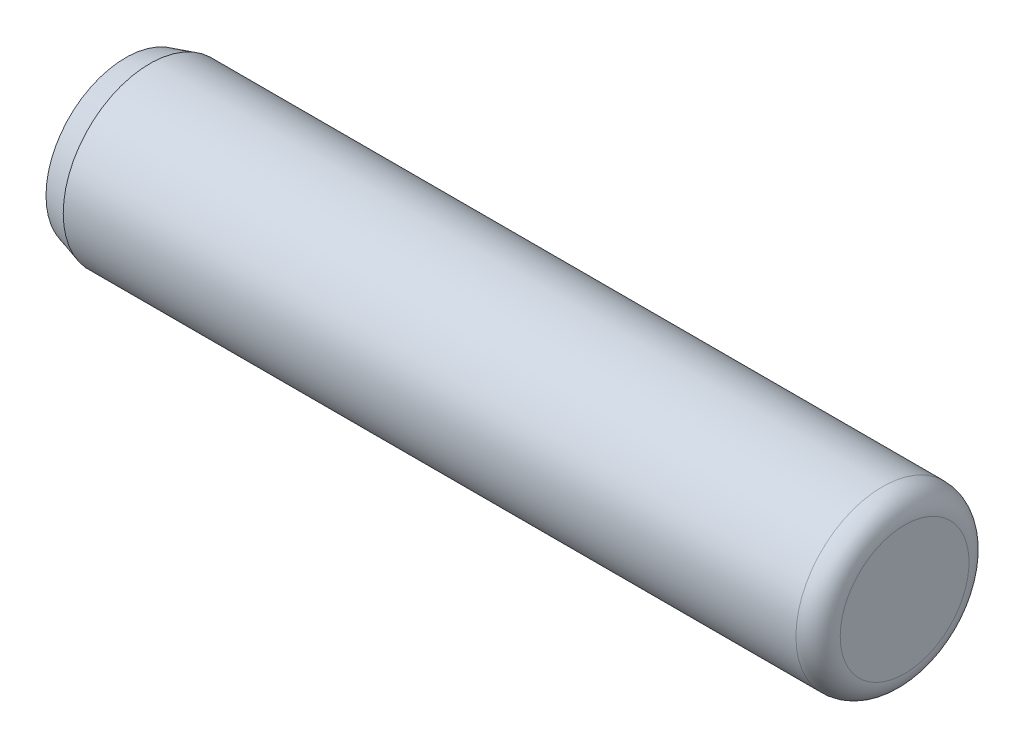
SolidWorks part; units mm, degrees
ref_plane "Front" through (0, 0, 0) normal (0, 0, 1) x (1, 0, 0)
ref_plane "Top" through (0, 0, 0) normal (0, 1, 0) x (1, 0, 0)
ref_plane "Right" through (0, 0, 0) normal (1, 0, 0) x (0, 0, -1)
sketch "Sketch1" plane through (0, 0, 0) normal (1, 0, 0) x (0, 0, -1)
  circle A0 centre (0, 0) radius 1.5875 construction
  point P3 (0, 1.5875)
  dimension "Diameter" = 3.175
sketch "Sketch2" plane through (0, 0, 0) normal (0, 0, 1) x (1, 0, 0)
  line L0 (-7.1438, 0) -> (7.1438, 0) construction
  line L1 (7.1438, 1.1811) -> (7.1438, -0.6481) construction
  line L2 (-7.1437, 1.4605) -> (-7.1437, -1.4605) construction
  line L3 (-7.1437, 1.4605) -> (-7.1437, 1.5875) construction
  line L4 (-7.1437, -1.4605) -> (-7.1437, -1.5875) construction
  line L5 (-7.1437, 1.4605) -> (-6.7008, 1.5875) construction
  line L6 (-6.7008, 1.5875) -> (6.7373, 1.5875) construction
  arc A0 (6.7373, 1.5875) -> (7.1438, 1.1811) centre (6.7373, 1.1811) cw construction
  point P6 (-3.9688, 0)
  point P8 (3.9688, 0)
  point P23 (6.1024, 1.5875)
  dimension "Crown Radius" = 0.4064
  dimension "Length" = 14.2875
  dimension "D1" = 3.175
  dimension "D2" = 3.175
  dimension "Point Diameter" = 2.921
  dimension "D3" = 16
  dimension "Crown Height" = 1.0414
sketch "Sketch3" plane through (0, 0, 0) normal (0, 0, 1) x (1, 0, 0)
  line L0 (7.1438, 1.1811) -> (7.1438, -0.6481) construction
  line L1 (-6.7008, 1.5875) -> (6.7373, 1.5875) construction
  line L2 (-7.1437, 1.4605) -> (-6.7008, 1.5875) construction
  line L3 (-7.1437, 1.4605) -> (-7.1437, -1.4605) construction
  line L4 (-7.1438, 0) -> (7.1438, 0) construction
  line L5 (7.1438, 1.1811) -> (7.1438, 0)
  line L6 (-6.7008, 1.5875) -> (6.7373, 1.5875)
  line L7 (-7.1437, 1.4605) -> (-6.7008, 1.5875)
  line L8 (-7.1437, 1.4605) -> (-7.1438, 0)
  line L9 (-7.1438, 0) -> (7.1438, 0)
  arc A0 (7.1438, 1.1811) -> (6.7373, 1.5875) centre (6.7373, 1.1811) ccw construction
  arc A1 (7.1438, 1.1811) -> (6.7373, 1.5875) centre (6.7373, 1.1811) ccw
revolve "Revolve1" add sketch "Sketch3" angle 360 about L0
equation "\"D1@Sketch2\" = \"Diameter@Sketch1\""
equation "\"D2@Sketch2\" = \"Diameter@Sketch1\""
